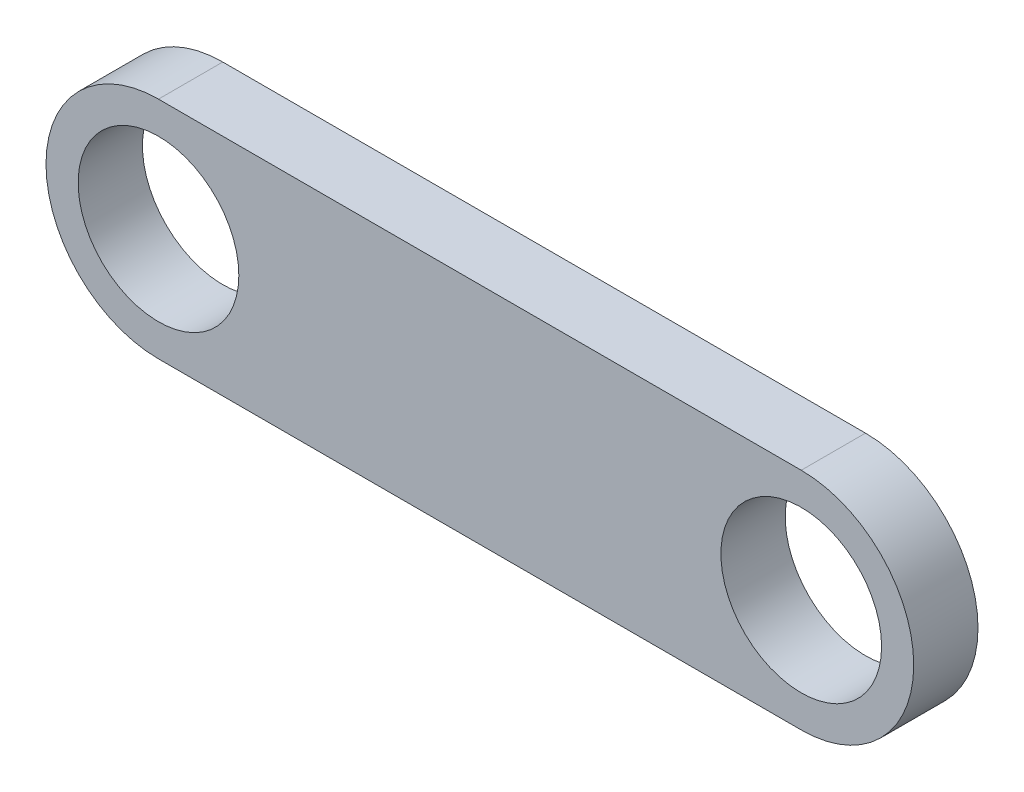
SolidWorks part; units mm, degrees
ref_plane "Спереди" through (0, 0, 0) normal (0, 0, 1) x (1, 0, 0)
ref_plane "Сверху" through (0, 0, 0) normal (0, 1, 0) x (1, 0, 0)
ref_plane "Справа" through (0, 0, 0) normal (1, 0, 0) x (0, 0, -1)
sketch "Эскиз1" plane through (0, 0, 0) normal (0, 0, 1) x (1, 0, 0)
  line L0 (0, 0) -> (200, 0) construction
  line L1 (0, 35) -> (200, 35)
  line L2 (0, -35) -> (200, -35)
  arc A0 (0, 35) -> (0, -35) centre (0, 0) ccw
  arc A1 (200, -35) -> (200, 35) centre (200, 0) ccw
  circle A2 centre (0, 0) radius 25
  circle A3 centre (200, 0) radius 25
  point P3 (100, 0)
  dimension "D1" = 200
extrude "Бобышка-Вытянуть1" add sketch "Эскиз1" along normal blind 20
